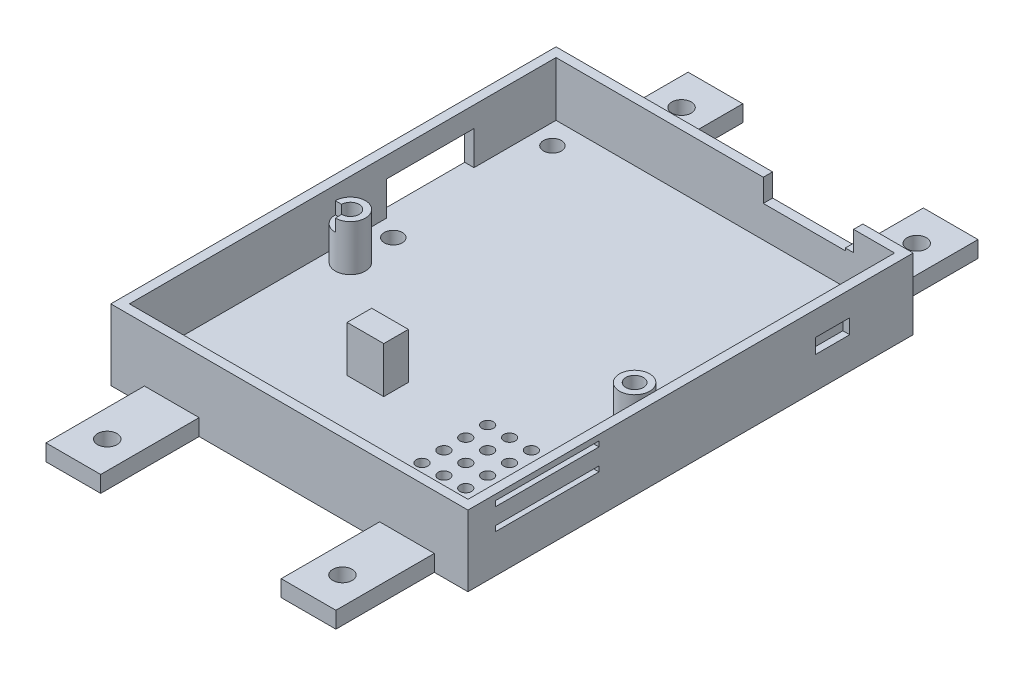
SolidWorks part; units mm, degrees
ref_plane "Front Plane" through (0, 0, 0) normal (0, 0, 1) x (1, 0, 0)
ref_plane "Top Plane" through (0, 0, 0) normal (0, 1, 0) x (1, 0, 0)
ref_plane "Right Plane" through (0, 0, 0) normal (1, 0, 0) x (0, 0, -1)
sketch "Sketch2" plane through (0, 0, 0) normal (0, 1, 0) x (1, 0, 0)
  line L0 (-34.5643, -72.3688) -> (-1.5643, -72.3688)
  line L1 (-50.7143, -72.3688) -> (-44.5643, -72.3688)
  line L2 (-50.7143, -72.3688) -> (-50.7143, 9.0312)
  line L3 (-50.7143, 9.0312) -> (-44.5643, 9.0312)
  line L4 (14.5857, -72.3688) -> (14.5857, 9.0312)
  line L5 (8.4357, 9.0312) -> (14.5857, 9.0312)
  line L6 (-44.5643, 9.0312) -> (-44.5643, 27.0312)
  line L7 (-44.5643, 27.0312) -> (-34.5643, 27.0312)
  line L8 (-34.5643, 9.0312) -> (-34.5643, 27.0312)
  line L10 (-1.5643, 9.0312) -> (-1.5643, 27.0312)
  line L11 (-1.5643, 27.0312) -> (8.4357, 27.0312)
  line L12 (8.4357, 9.0312) -> (8.4357, 27.0312)
  line L13 (8.4357, -72.3688) -> (14.5857, -72.3688)
  line L14 (-44.5643, -72.3688) -> (-44.5643, -90.3688)
  line L15 (-44.5643, -90.3688) -> (-34.5643, -90.3688)
  line L16 (-34.5643, -72.3688) -> (-34.5643, -90.3688)
  line L17 (-34.5643, 9.0312) -> (-1.5643, 9.0312)
  line L18 (-1.5643, -72.3688) -> (-1.5643, -90.3688)
  line L19 (-1.5643, -90.3688) -> (8.4357, -90.3688)
  line L20 (8.4357, -72.3688) -> (8.4357, -90.3688)
  dimension "D1" = 65.3
  dimension "D2" = 81.4
  dimension "D3" = 18
  dimension "D4" = 10
  dimension "D5" = 33
extrude "Boss-Extrude1" add sketch "Sketch2" along normal blind 3
sketch "Sketch3" plane through (0, 3, 0) normal (0, 1, 0) x (1, 0, 0)
  line L0 (-49.0143, -70.6688) -> (-49.0143, 7.3312)
  line L1 (-49.0143, 7.3312) -> (12.8857, 7.3312)
  line L2 (12.8857, 7.3312) -> (12.8857, -70.6688)
  line L3 (12.8857, -70.6688) -> (-49.0143, -70.6688)
  line L4 (-50.7143, -72.3688) -> (-50.7143, 9.0312)
  line L5 (-50.7143, 9.0312) -> (14.5857, 9.0312)
  line L6 (14.5857, 9.0312) -> (14.5857, -72.3688)
  line L7 (14.5857, -72.3688) -> (-50.7143, -72.3688)
  dimension "D1" = 1.7
  dimension "D2" = 1.7
  dimension "D3" = 1.7
  dimension "D4" = 1.7
extrude "Boss-Extrude2" add sketch "Sketch3" along normal blind 9.94
sketch "Sketch4" plane through (0, 3, 0) normal (0, 1, 0) x (1, 0, 0)
  line L0 (-45.3143, -26.1188) -> (-45.3143, 2.9812) construction
  line L1 (-27.7143, -47.6688) -> (-21.0143, -47.6688)
  line L2 (-27.7143, -47.6688) -> (-27.7143, -52.1688)
  line L3 (-27.7143, -52.1688) -> (-21.0143, -52.1688)
  line L4 (-21.0143, -47.6688) -> (-21.0143, -52.1688)
  line L5 (-45.3143, 2.9812) -> (7.8857, 2.9812) construction
  line L6 (7.8857, 2.9812) -> (7.8857, -26.1188) construction
  line L7 (7.8857, -26.1188) -> (-45.3143, -26.1188) construction
  line L8 (-49.0143, 7.3312) -> (-49.0143, -70.6688) construction
  line L9 (12.8857, 7.3312) -> (-49.0143, 7.3312) construction
  line L13 (-49.0143, 7.3312) -> (-49.0143, -70.6688) construction
  line L14 (-49.0143, -70.6688) -> (12.8857, -70.6688) construction
  circle A0 centre (-45.3143, 2.9812) radius 1.65
  circle A1 centre (-45.3143, -26.1188) radius 1.65
  circle A2 centre (7.8857, 2.9812) radius 1.65
  circle A3 centre (7.8857, -26.1188) radius 1.65
  circle A4 centre (-45.3143, -33.9688) radius 1.6
  circle A5 centre (8.08, -35.3988) radius 1.6
  dimension "D5" = 3.3
  dimension "D12" = 3.2
  dimension "D1" = 29.1
  dimension "D2" = 53.2
  dimension "D3" = 3.7
  dimension "D4" = 4.35
  dimension "D6" = 28
  dimension "D7" = 23
  dimension "D8" = 6.7
  dimension "D9" = 4.5
  dimension "D10" = 7.85
  dimension "D11" = 53.3943
  dimension "D13" = 38.38
extrude "Cut-Extrude1" cut sketch "Sketch4" against normal through all
sketch "Sketch5" plane through (0, 3, 0) normal (0, 1, 0) x (1, 0, 0)
  line L1 (-27.7143, -52.1688) -> (-21.0143, -52.1688)
  line L2 (-27.7143, -52.1688) -> (-27.7143, -47.6688)
  line L3 (-27.7143, -47.6688) -> (-21.0143, -47.6688)
  line L4 (-21.0143, -52.1688) -> (-21.0143, -47.6688)
extrude "Boss-Extrude3" add sketch "Sketch5" along normal blind 10.15 and the other way up to surface (3 mm away) separate body other way up to face at (8.08, 0, 33.7988)
sketch "Sketch6" plane through (0, 3, 0) normal (0, 1, 0) x (1, 0, 0)
  circle A0 centre (-45.3143, -33.9688) radius 2.75
  circle A1 centre (8.08, -35.3988) radius 2.75
  circle A2 centre (-45.3143, -33.9688) radius 1.6 construction
  circle A3 centre (8.08, -35.3988) radius 1.6 construction
  dimension "D1" = 5.5
extrude "Boss-Extrude4" add sketch "Sketch6" along normal blind 10.15 separate body
sketch "Sketch7" plane through (0, 13.15, 0) normal (0, 1, 0) x (1, 0, 0)
  line L0 (-48.0643, -33.9688) -> (-45.3143, -33.9688)
  line L1 (-45.3143, -33.9688) -> (-45.3143, -36.7188)
  arc A0 (-48.0643, -33.9688) -> (-45.3143, -36.7188) centre (-45.3143, -33.9688) ccw
  circle A3 centre (-45.3143, -33.9688) radius 2.75 construction
extrude "Cut-Extrude2" cut sketch "Sketch7" against normal blind 4
sketch "Sketch17" plane through (0, 13.15, 0) normal (0, 1, 0) x (1, 0, 0)
  circle A0 centre (-45.3143, -33.9688) radius 1.6
  circle A1 centre (8.08, -35.3988) radius 1.6
  circle A2 centre (8.08, -35.3988) radius 2.75 construction
  dimension "D1" = 3.2
extrude "Cut-Extrude11" cut sketch "Sketch17" against normal through all
sketch "Sketch19" plane through (-49.0143, 0, 0) normal (1, 0, 0) x (0, 0, -1)
  line L0 (7.3312, 3) -> (-70.6688, 3) construction
  line L1 (-23.6688, 3) -> (-7.6688, 3)
  line L2 (-23.6688, 3) -> (-23.6688, 9.2)
  line L3 (-23.6688, 9.2) -> (-7.6688, 9.2)
  line L4 (-7.6688, 3) -> (-7.6688, 9.2)
  line L5 (-15.6688, 9.2) -> (-15.6688, 3) construction
  line L7 (7.3312, 12.94) -> (7.3312, 3) construction
  dimension "D1" = 16
  dimension "D2" = 15
  dimension "D3" = 6.2
extrude "Cut-Extrude12" cut sketch "Sketch19" against normal through all
sketch "Sketch20" plane through (0, 0, -7.3312) normal (0, 0, 1) x (1, 0, 0)
  line L0 (12.8857, 12.94) -> (-49.0143, 12.94) construction
  line L1 (-11.1143, 12.94) -> (3.8857, 12.94)
  line L2 (-11.1143, 12.94) -> (-11.1143, 8.79)
  line L3 (-11.1143, 8.79) -> (3.8857, 8.79)
  line L4 (3.8857, 12.94) -> (3.8857, 8.79)
  dimension "D1" = 9
  dimension "D2" = 15
  dimension "D3" = 4.15
extrude "Cut-Extrude13" cut sketch "Sketch20" against normal through all
sketch "Sketch21" plane through (0, 13.15, 0) normal (0, 1, 0) x (1, 0, 0)
  circle A0 centre (-45.3143, -33.9688) radius 2.75
  arc A1 (-45.3143, -36.7188) -> (-48.0643, -33.9688) centre (-45.3143, -33.9688) ccw construction
extrude "Cut-Extrude14" cut sketch "Sketch21" against normal blind 1.75
sketch "Sketch22" plane through (0, 13.15, 0) normal (0, 1, 0) x (1, 0, 0)
  circle A0 centre (8.08, -35.3988) radius 2.75
  circle A1 centre (8.08, -35.3988) radius 1.6 construction
  circle A2 centre (8.08, -35.3988) radius 2.75 construction
extrude "Cut-Extrude15" cut sketch "Sketch22" against normal blind 1.75
sketch "Sketch23" plane through (0, 13.15, 0) normal (0, 1, 0) x (1, 0, 0)
  line L1 (-27.7143, -52.1688) -> (-21.0143, -52.1688)
  line L2 (-27.7143, -52.1688) -> (-27.7143, -47.6688)
  line L3 (-27.7143, -47.6688) -> (-21.0143, -47.6688)
  line L4 (-21.0143, -52.1688) -> (-21.0143, -47.6688)
extrude "Cut-Extrude16" cut sketch "Sketch23" against normal blind 1.75
sketch "Sketch10" plane through (0, 3, 0) normal (0, 1, 0) x (1, 0, 0)
  circle A0 centre (-7.0166, -47.1688) radius 1.05
  circle A1 centre (-3.0166, -47.1688) radius 1.05
  circle A2 centre (0.9834, -47.1688) radius 1.05
  circle A3 centre (4.9834, -47.1688) radius 1.05
  circle A4 centre (8.9834, -47.1688) radius 1.05
  circle A5 centre (-3.0166, -51.1688) radius 1.05
  circle A6 centre (0.9834, -51.1688) radius 1.05
  circle A7 centre (4.9834, -51.1688) radius 1.05
  circle A8 centre (8.9834, -51.1688) radius 1.05
  circle A9 centre (-3.0166, -55.1688) radius 1.05
  circle A10 centre (0.9834, -55.1688) radius 1.05
  circle A11 centre (4.9834, -55.1688) radius 1.05
  circle A12 centre (8.9834, -55.1688) radius 1.05
  circle A13 centre (-3.0166, -59.1688) radius 1.05
  circle A14 centre (0.9834, -59.1688) radius 1.05
  circle A15 centre (4.9834, -59.1688) radius 1.05
  circle A16 centre (8.9834, -59.1688) radius 1.05
  circle A17 centre (-7.0166, -51.1688) radius 1.05
  circle A18 centre (-7.0166, -55.1688) radius 1.05
  circle A19 centre (-7.0166, -59.1688) radius 1.05
  dimension "D3" = 2.1
  dimension "D1" = 5
  dimension "D2" = 4
extrude "Cut-Extrude5" cut sketch "Sketch10" against normal through all
sketch "Sketch11" plane through (14.5857, 0, 0) normal (1, 0, 0) x (0, 0, -1)
  line L0 (9.0312, 12.94) -> (9.0312, 0) construction
  line L1 (-8.8688, 5.8) -> (-2.5688, 5.8)
  line L2 (-8.8688, 5.8) -> (-8.8688, 8.5)
  line L3 (-8.8688, 8.5) -> (-2.5688, 8.5)
  line L4 (-2.5688, 5.8) -> (-2.5688, 8.5)
  line L5 (-72.3688, 0) -> (9.0312, 0) construction
  dimension "D1" = 11.6
  dimension "D2" = 6.3
  dimension "D3" = 2.7
  dimension "D4" = 5.8
extrude "Cut-Extrude6" cut sketch "Sketch11" against normal blind 1.25
sketch "Sketch15" plane through (0, 0, -7.3312) normal (0, 0, 1) x (1, 0, 0)
  line L0 (12.8857, 12.94) -> (3.8857, 12.94) construction
  line L1 (-10.7143, 12.94) -> (5.3857, 12.94)
  line L2 (-10.7143, 12.94) -> (-10.7143, 9.24)
  line L3 (-10.7143, 9.24) -> (5.3857, 9.24)
  line L4 (5.3857, 12.94) -> (5.3857, 9.24)
  dimension "D1" = 7.5
  dimension "D2" = 16.1
  dimension "D3" = 3.7
extrude "Cut-Extrude9" cut sketch "Sketch15" against normal through all
sketch "Sketch16" plane through (14.5857, 0, 0) normal (1, 0, 0) x (0, 0, -1)
  line L0 (-72.3688, 0) -> (9.0312, 0) construction
  line L1 (-67.3688, 11.9101) -> (-48.4126, 11.9101)
  line L2 (-67.3688, 11.9101) -> (-67.3688, 10.9551)
  line L3 (-67.3688, 10.9551) -> (-48.4126, 10.9551)
  line L4 (-48.4126, 11.9101) -> (-48.4126, 10.9551)
  line L5 (-67.3688, 7.9551) -> (-48.4126, 7.9551)
  line L6 (-67.3688, 7.9551) -> (-67.3688, 7)
  line L7 (-67.3688, 7) -> (-48.4126, 7)
  line L8 (-48.4126, 7.9551) -> (-48.4126, 7)
  line L9 (-72.3688, 12.94) -> (-72.3688, 0) construction
  dimension "D1" = 3
  dimension "D2" = 7
  dimension "D3" = 5
extrude "Cut-Extrude10" cut sketch "Sketch16" against normal up to surface (1.7 mm away) up to face at (12.8857, 7.97, 31.6688)
sketch "Sketch24" plane through (0, 3, 0) normal (0, 1, 0) x (1, 0, 0)
  line L0 (-39.5643, -84.1688) -> (-39.5643, 20.8312) construction
  line L1 (-39.5643, 20.8312) -> (3.4357, 20.8312) construction
  line L2 (3.4357, 20.8312) -> (3.4357, -84.1688) construction
  line L3 (3.4357, -84.1688) -> (-39.5643, -84.1688) construction
  line L4 (-18.1885, 9.0312) -> (-18.1885, 20.8312) construction
  line L5 (-11.1143, 9.0312) -> (-50.7143, 9.0312) construction
  line L6 (-18.0643, -84.1688) -> (-18.0643, -72.3688) construction
  line L7 (-50.7143, -72.3688) -> (14.5857, -72.3688) construction
  line L8 (-44.5643, -74.5602) -> (-39.5643, -74.5602) construction
  line L9 (-44.5643, -72.3688) -> (-44.5643, -90.3688) construction
  line L10 (-39.5643, -74.5602) -> (-34.5643, -74.5602) construction
  line L11 (-34.5643, -90.3688) -> (-34.5643, -72.3688) construction
  line L12 (-1.5643, -74.4133) -> (3.4357, -74.4133) construction
  line L14 (3.4357, -74.4133) -> (8.4357, -74.4133) construction
  line L15 (8.4357, -90.3688) -> (8.4357, -72.3688) construction
  line L16 (-1.5643, -72.3688) -> (-1.5643, -90.3688) construction
  circle A0 centre (-39.5643, 20.8312) radius 1.775
  circle A1 centre (3.4357, 20.8312) radius 1.775
  circle A2 centre (3.4357, -84.1688) radius 1.775
  circle A3 centre (-39.5643, -84.1688) radius 1.775
  dimension "D1" = 3.55
  dimension "D2" = 105
  dimension "D3" = 43
extrude "Cut-Extrude17" cut sketch "Sketch24" against normal through all
